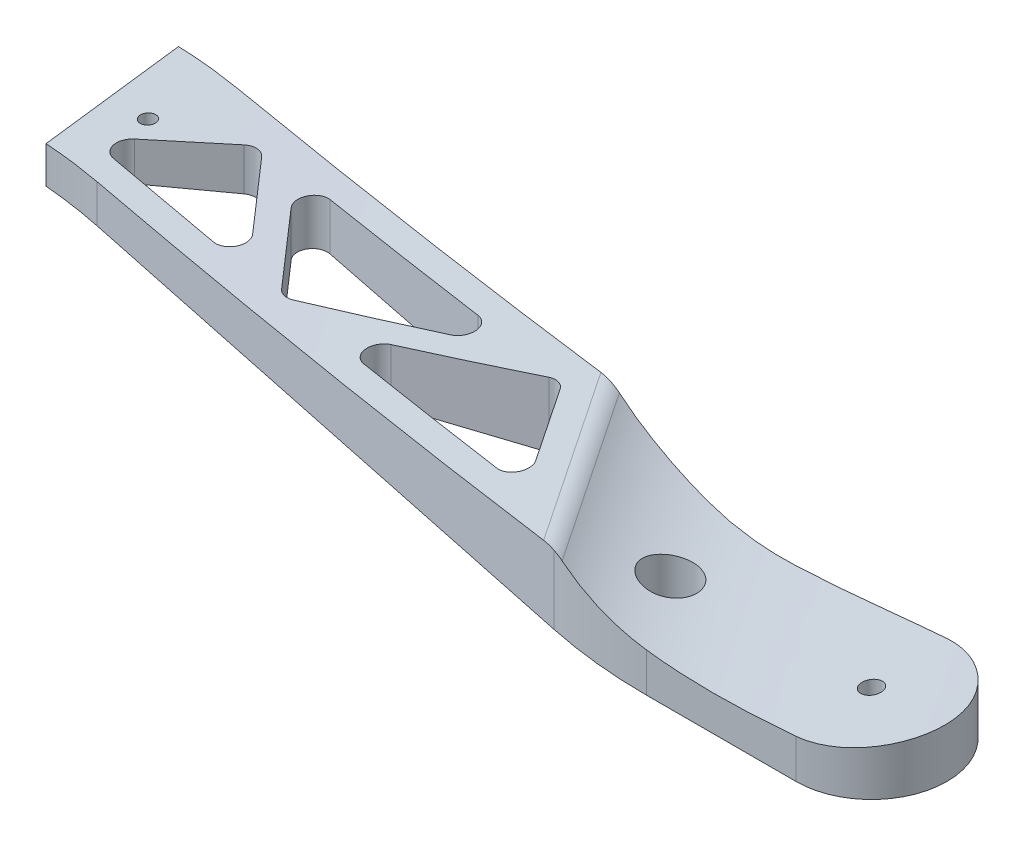
SolidWorks part; units mm, degrees
ref_plane "Front Plane" through (0, 0, 0) normal (0, 0, 1) x (1, 0, 0)
ref_plane "Top Plane" through (0, 0, 0) normal (0, 1, 0) x (1, 0, 0)
ref_plane "Right Plane" through (0, 0, 0) normal (1, 0, 0) x (0, 0, -1)
sketch "Sketch1" plane through (0, 0, 0) normal (0, 1, 0) x (1, 0, 0)
  line L0 (0, 0) -> (-350, 0) construction
  line L1 (0, 0) -> (40, 0) construction
  line L2 (0, 15) -> (40, 15)
  line L3 (0, -15) -> (40, -15)
  line L4 (-351.8754, 29.9413) -> (-333.2857, -24.9125) construction
  line L5 (-139.7849, 43.2259) -> (-4217.6379, -212.1962)
  line L6 (0, 15) -> (-4004.6012, 823.6244)
  line L7 (0, 15) -> (-5.9197, -13.7825) construction
  line L8 (-4217.6379, -212.1962) -> (-138.0533, 13.889)
  line L9 (-4004.6012, 823.6244) -> (-5.9197, -13.7825)
  line L10 (-333.2857, -24.9125) -> (-287.8235, 5.5889)
  line L11 (-5.9197, -13.7825) -> (0, -15)
  circle A0 centre (0, 0) radius 5
  circle A1 centre (-350, 0) radius 30
  circle A2 centre (40, 0) radius 2
  circle A3 centre (0, 0) radius 15
  circle A4 centre (40, 0) radius 15
  dimension "D1" = 10
  dimension "D4" = 4
  dimension "D5" = 60
  dimension "D6" = 30
  dimension "D7" = 165
  dimension "D2" = 350
  dimension "D3" = 40
  dimension "D8" = 165
  dimension "D9" = 135
  dimension "D10" = 150
extrude "Boss-Extrude1" add sketch "Sketch1" along normal blind 20 contours L8 A1 | A1 L8 | A1 L8 L9 L5 | A1 L10 L8 | A3 L6 L5 L9 | A3 A0 | A4 L2 A3 L3 | A4 A2
fillet "Fillet1" radius 100 5 edges at (0, 10, -15) (-139.7849, 10, -43.2259) (-138.0533, 10, -13.889) (-287.8235, 10, -5.5889) (0, 10, 15)
ref_plane "Plane1" through (-86.3568, 0, -128.7144) normal (0.5571, 0, 0.8304) x (0.8304, 0, -0.5571)
sketch "Sketch3" plane through (-86.3568, 0, -128.7144) normal (0.5571, 0, 0.8304) x (0.8304, 0, -0.5571)
  line L0 (-290.646, 20) -> (-290.646, 0) construction
  line L1 (-290.646, 20) -> (-263.3377, 20) construction
  line L2 (-290.646, 20) -> (0.1568, 20)
  line L4 (48.2167, 0) -> (48.2167, 20) construction
  line L5 (0.1568, 20) -> (48.2167, 20)
  line L6 (48.2167, 20) -> (48.2167, 10)
  line L11 (0.1568, 20) -> (0.1568, 0) construction
  line L13 (48.2167, 0) -> (48.2167, 20) construction
  line L14 (48.2167, 7) -> (-242.9986, 7) construction
  line L15 (-15.6816, 0) -> (-15.6816, 20) construction
  spline S0 degree 2 poles (-290.646, 20) (-152.5347, -2.5394) (-15.6816, 14) knots 0 0 0 1 1 1
  spline S1 degree 3 poles (-15.6816, 14) (1.7787, 1.081) (32.0315, 10) (48.2167, 10) knots 0 0 0 0 1 1 1 1
  point P4 (48.2167, 7)
  dimension "D2" = 6
  dimension "D1" = 10
  dimension "D3" = 7
extrude "Cut-Extrude3" cut sketch "Sketch3" along normal blind 300 and the other way blind 131
fillet "Fillet3" radius 5 1 edges at (-21.8644, 14, -4.4422)
sketch "Sketch4" plane through (0, 0, 0) normal (0, 1, 0) x (1, 0, 0)
  line L0 (-23.8661, -4.9157) -> (-39.1031, 17.7949)
  line L1 (-39.1031, 17.7949) -> (-75.6397, 5.9268)
  line L2 (-75.6397, 5.9268) -> (-23.8661, -4.9157)
  line L3 (-125.1676, 11.1905) -> (-12.8731, -12.3263) construction
  line L4 (-12.8731, -12.3263) -> (-36.0971, 22.2889) construction
  line L5 (-49.0834, 19.8102) -> (-105.8384, 31.2704)
  line L6 (-105.8384, 31.2704) -> (-85.48, 7.9875)
  line L7 (-85.48, 7.9875) -> (-49.0834, 19.8102)
  line L8 (-36.0971, 22.2889) -> (-126.8801, 40.6201) construction
  line L9 (-113.9044, 32.8991) -> (-93.6107, 9.6903)
  line L10 (-93.6107, 9.6903) -> (-134.1835, 18.1871)
  line L11 (-134.1835, 18.1871) -> (-113.9044, 32.8991)
  line L12 (-127.4003, 35.6242) -> (-14.8981, 12.9074) construction
  line L13 (-134.1835, 18.1871) -> (-23.8661, -4.9157) construction
  line L14 (-150.6827, 37.5335) -> (-354.5716, 24.7626) construction
  line L15 (-143.9898, 18.5677) -> (-279.6875, 11.0475) construction
  line L16 (-260.4276, 7.1072) -> (-151.1984, 13.1605) construction
  line L17 (-152.9244, 42.4029) -> (-351.8754, 29.9413) construction
  line L18 (-143.9898, 18.5677) -> (-162.2437, 36.8094)
  line L19 (-162.2437, 36.8094) -> (-173.6392, 16.9246)
  line L20 (-173.6392, 16.9246) -> (-143.9898, 18.5677)
  line L21 (-168.2211, 36.435) -> (-179.5911, 16.5947)
  line L22 (-179.5911, 16.5947) -> (-198.1353, 34.5613)
  line L23 (-198.1353, 34.5613) -> (-168.2211, 36.435)
  line L24 (-186.3879, 16.218) -> (-204.8846, 34.1385)
  line L25 (-204.8846, 34.1385) -> (-219.6625, 14.374)
  line L26 (-219.6625, 14.374) -> (-186.3879, 16.218)
  line L27 (-211.4344, 33.7282) -> (-226.1755, 14.0131)
  line L28 (-226.1755, 14.0131) -> (-242.9353, 31.7551)
  line L29 (-242.9353, 31.7551) -> (-211.4344, 33.7282)
  line L30 (-232.7115, 13.6509) -> (-279.6875, 11.0475)
  line L31 (-279.6875, 11.0475) -> (-249.4292, 31.3484)
  line L32 (-249.4292, 31.3484) -> (-232.7115, 13.6509)
  line L33 (-150.6827, 37.5335) -> (-143.9898, 18.5677) construction
  line L34 (-143.9898, 18.5677) -> (-134.1835, 18.1871) construction
  line L35 (-127.4003, 35.6242) -> (-134.1835, 18.1871) construction
  line L37 (-259.3276, 30.7284) -> (-327.7673, -15.189)
  line L38 (-327.7673, -15.189) -> (-354.5716, 24.7626)
  line L39 (-366.7143, 24.9125) -> (-333.2857, -24.9125) construction
  line L40 (-333.2857, -24.9125) -> (-310.6084, -9.6979) construction
  line L41 (-354.5716, 24.7626) -> (-259.3276, 30.7284)
  line L42 (-364.7467, 9.4158) -> (-348.0325, -15.4967) construction
  circle A0 centre (-147.3362, 28.0506) radius 1.5
  circle A1 centre (-130.7919, 26.9057) radius 1.5
  circle A2 centre (-364.7467, 9.4158) radius 1.5
  circle A3 centre (-348.0325, -15.4967) radius 1.5
  dimension "D12" = 3
  dimension "D13" = 3
  dimension "D1" = 5
  dimension "D2" = 5
  dimension "D3" = 5
  dimension "D4" = 5
  dimension "D5" = 5
  dimension "D6" = 5
  dimension "D7" = 5
  dimension "D8" = 5
  dimension "D9" = 5
  dimension "D10" = 5
  dimension "D11" = 5
  dimension "D14" = 10
  dimension "D15" = 5
  dimension "D16" = 5
  dimension "D17" = 7
  dimension "D18" = 30
extrude "Cut-Extrude4" cut sketch "Sketch4" along normal blind 114 contours L41 L37 L38 | L32 L30 L31 | L29 L27 L28 | L26 L24 L25 | L23 L21 L22 | L20 L18 L19 | A1 | A0 | L11 L9 L10 | L7 L5 L6 | L2 L0 L1 | A3 | A2
fillet "Fillet4" radius 3 27 edges at (-23.8661, 6.5969, 4.9157) (-75.6397, 4.8538, -5.9268) (-39.1031, 6.5969, -17.7949) (-49.0834, 6.2031, -19.8102) (-85.48, 4.6031, -7.9875) (-105.8384, 4.4739, -31.2704) (-93.6107, 4.4153, -9.6903) (-134.1835, 3.7402, -18.1871) (-113.9044, 4.2984, -32.8991) (-143.9898, 3.6314, -18.5677) (-173.6392, 3.5024, -16.9246) (-162.2437, 3.5795, -36.8094) (-179.5911, 3.5172, -16.5947) (-198.1353, 3.5474, -34.5613) (-168.2211, 3.5395, -36.435) (-204.8846, 3.5971, -34.1385) (-186.3879, 3.5507, -16.218) (-219.6625, 3.9702, -14.374) (-242.9353, 4.2066, -31.7551) (-226.1755, 4.1019, -14.0131) (-211.4344, 3.6621, -33.7282) (-279.6875, 5.7968, -11.0475) (-232.7115, 4.2504, -13.6509) (-249.4292, 4.3664, -31.3484) (-259.3276, 4.6413, -30.7284) (-354.5716, 9.2095, -24.7626) (-327.7673, 9.2095, 15.189)
sketch "Sketch5" plane through (0, 0, 0) normal (0, 1, 0) x (1, 0, 0)
  line L0 (0, 131.8931) -> (0, -132.9054) construction
  line L1 (-149.5876, 131.7171) -> (-120.5615, -144.4481)
  line L2 (0, 0) -> (-8.1263, 77.3162) construction
  line L3 (-149.5876, 131.7171) -> (-434.6413, 42.4032)
  line L4 (-434.6413, 42.4032) -> (-303.3894, -167.7836)
  line L5 (-303.3894, -167.7836) -> (-120.5615, -144.4481)
  dimension "D1" = 6
  dimension "D2" = 135
extrude "Cut-Extrude5" cut sketch "Sketch5" along normal blind 133
